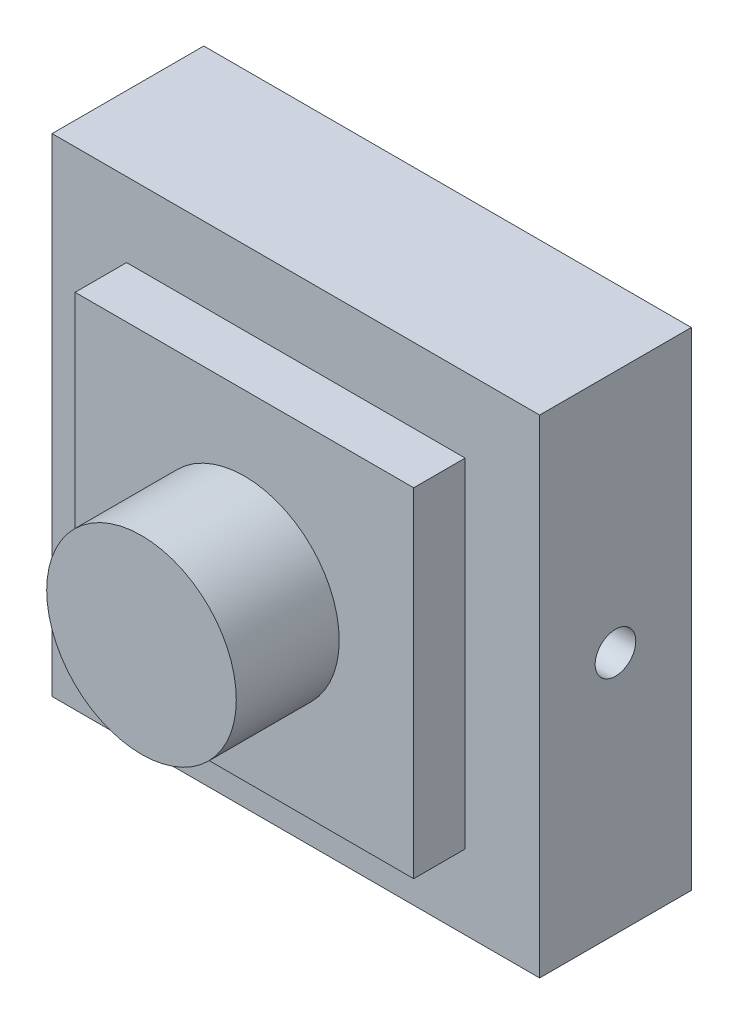
SolidWorks part; units mm, degrees
ref_plane "前视基准面" through (0, 0, 0) normal (0, 0, 1) x (1, 0, 0)
ref_plane "上视基准面" through (0, 0, 0) normal (0, 1, 0) x (1, 0, 0)
ref_plane "右视基准面" through (0, 0, 0) normal (1, 0, 0) x (0, 0, -1)
sketch "草图2" plane through (0, 0, 0) normal (0, 0, 1) x (1, 0, 0)
  line L1 (18, -18) -> (-18, -18)
  line L2 (18, -18) -> (18, 18)
  line L3 (18, 18) -> (-18, 18)
  line L4 (-18, -18) -> (-18, 18)
  line L5 (18, -18) -> (-18, 18) construction
  line L6 (18, 18) -> (-18, -18) construction
  point P0 (0, 0)
  dimension "D1" = 36
  dimension "D2" = 36
extrude "凸台-拉伸1" add sketch "草图2" along normal blind 11.2
sketch "草图3" plane through (0, 0, 11.2) normal (0, 0, 1) x (1, 0, 0)
  line L1 (12.5, -12.5) -> (-12.5, -12.5)
  line L2 (12.5, -12.5) -> (12.5, 12.5)
  line L3 (12.5, 12.5) -> (-12.5, 12.5)
  line L4 (-12.5, -12.5) -> (-12.5, 12.5)
  line L5 (12.5, -12.5) -> (-12.5, 12.5) construction
  line L6 (12.5, 12.5) -> (-12.5, -12.5) construction
  point P0 (0, 0)
  dimension "D1" = 25
  dimension "D2" = 25
extrude "凸台-拉伸2" add sketch "草图3" along normal blind 3.8
sketch "草图4" plane through (0, 0, 15) normal (0, 0, 1) x (1, 0, 0)
  circle A0 centre (0, 0) radius 7
  dimension "D1" = 14
extrude "凸台-拉伸3" add sketch "草图4" along normal blind 7.6
hole_wizard "M3 螺纹孔1" positions "草图5" profile "草图6" tap size "M3" standard "GB"
sketch "草图5" plane through (-18, 0, 0) normal (-1, 0, 0) x (0, 0, 1)
  line L0 (11.2, 18) -> (0, 18) construction
  point P0 (5.6, 0)
  point P6 (5.6, 18)
sketch "草图6" plane through (-18, 0, 5.6) normal (0, 1, 0) x (0, 0, 1)
  line L0 (0, 0) -> (0, 8.2511)
  line L1 (0, 8.2511) -> (1.25, 7.5)
  line L2 (1.25, 7.5) -> (1.25, 6)
  line L3 (1.25, 6) -> (1.5, 6)
  line L4 (1.5, 6) -> (1.5, 0)
  line L5 (1.5, 0) -> (0, 0)
  line L10 (0, 8.2511) -> (-1.25, 7.5) construction
  line L11 (0, -6.35) -> (0, 107.95) construction
  dimension "螺纹孔钻头直径" = 2.5
  dimension "螺纹孔钻头深度" = 7.5
  dimension "螺纹主直径" = 3
  dimension "螺纹深度" = 6
  dimension "导头角度" = 118
mirror "镜向1" about plane through (0, 0, 0) normal (1, 0, 0) of "M3 螺纹孔1"
